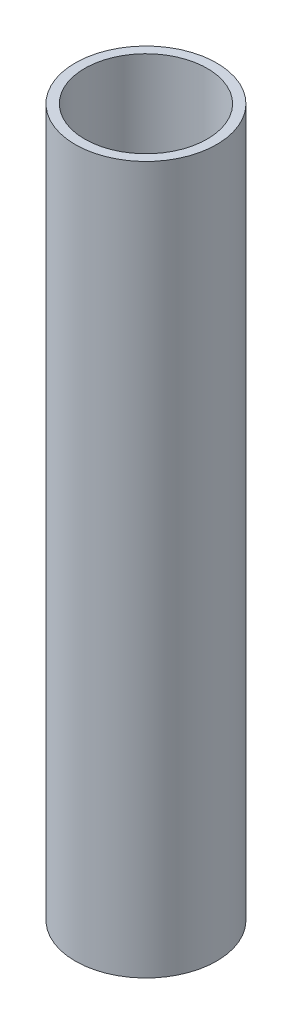
SolidWorks part; units mm, degrees
ref_plane "Front Plane" through (0, 0, 0) normal (0, 0, 1) x (1, 0, 0)
ref_plane "Top Plane" through (0, 0, 0) normal (0, 1, 0) x (1, 0, 0)
ref_plane "Right Plane" through (0, 0, 0) normal (1, 0, 0) x (0, 0, -1)
sketch "Sketch1" plane through (0, 0, 0) normal (0, 1, 0) x (1, 0, 0)
  circle A0 centre (0, 0) radius 7.5
  circle A1 centre (0, 0) radius 6.5
  dimension "D1" = 15
  dimension "D2" = 13
extrude "Boss-Extrude1" add sketch "Sketch1" along normal mid plane 75
